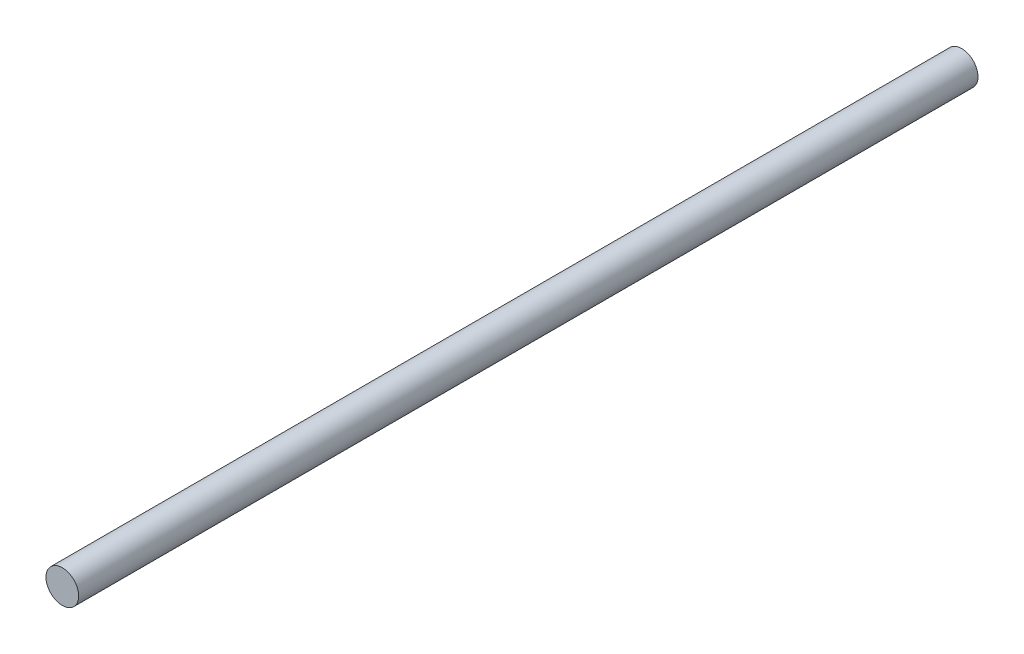
SolidWorks part; units mm, degrees
material "Nickel"
ref_plane "Front Plane" through (0, 0, 0) normal (0, 0, 1) x (1, 0, 0)
ref_plane "Top Plane" through (0, 0, 0) normal (0, 1, 0) x (1, 0, 0)
ref_plane "Right Plane" through (0, 0, 0) normal (1, 0, 0) x (0, 0, -1)
sketch "Sketch1" plane through (0, 0, 0) normal (0, 0, 1) x (1, 0, 0)
  circle A0 centre (-5.9871, 4.9645) radius 4
  dimension "D1" = 8
extrude "Boss-Extrude1" add sketch "Sketch1" along normal blind 220
